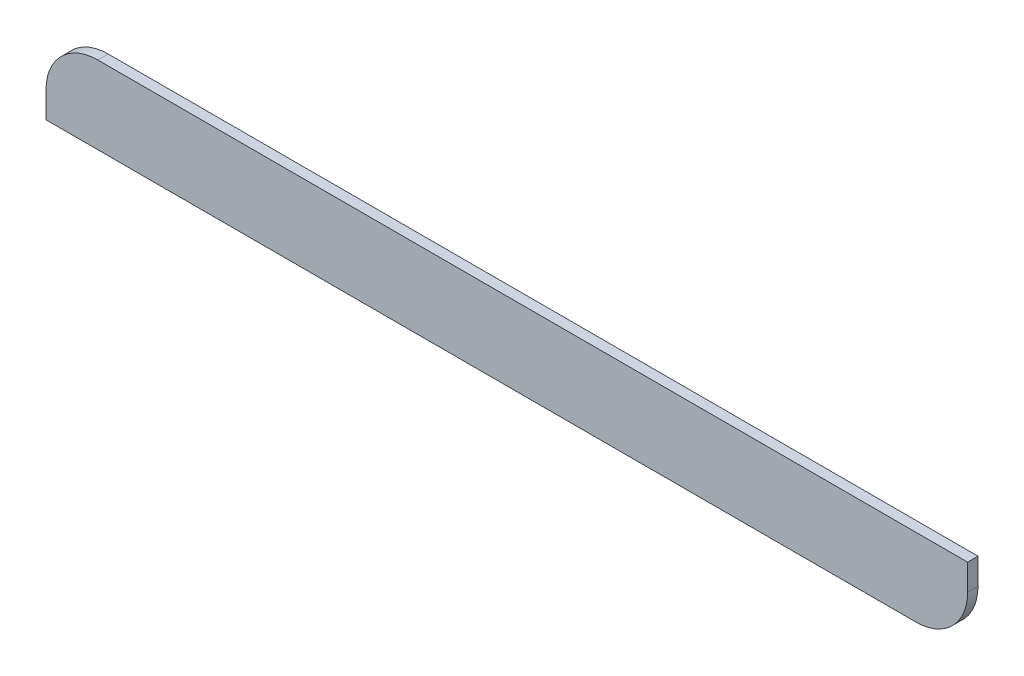
SolidWorks part; units mm, degrees
ref_plane "Front Plane" through (0, 0, 0) normal (0, 0, 1) x (1, 0, 0)
ref_plane "Top Plane" through (0, 0, 0) normal (0, 1, 0) x (1, 0, 0)
ref_plane "Right Plane" through (0, 0, 0) normal (1, 0, 0) x (0, 0, -1)
sketch "Sketch1" plane through (0, 0, 0) normal (0, 0, 1) x (1, 0, 0)
  line L1 (-160.9739, -6.8619) -> (6.8261, -6.8619)
  line L2 (-170.9739, -16.8619) -> (-170.9739, -21.8619)
  line L3 (-170.9739, -21.8619) -> (-3.1739, -21.8619)
  line L4 (6.8261, -6.8619) -> (6.8261, -11.8619)
  line L5 (-170.9739, -6.8619) -> (6.8261, -21.8619) construction
  line L6 (-170.9739, -21.8619) -> (6.8261, -6.8619) construction
  arc A0 (-3.1739, -21.8619) -> (6.8261, -11.8619) centre (-3.1739, -11.8619) ccw
  arc A1 (-160.9739, -6.8619) -> (-170.9739, -16.8619) centre (-160.9739, -16.8619) ccw
  point P0 (-82.0739, -14.3619)
  dimension "D3" = 10
  dimension "D1" = 15
  dimension "D2" = 177.8
extrude "Boss-Extrude1" add sketch "Sketch1" along normal blind 2 contours L1 L4 A0 L3 L2 A1
